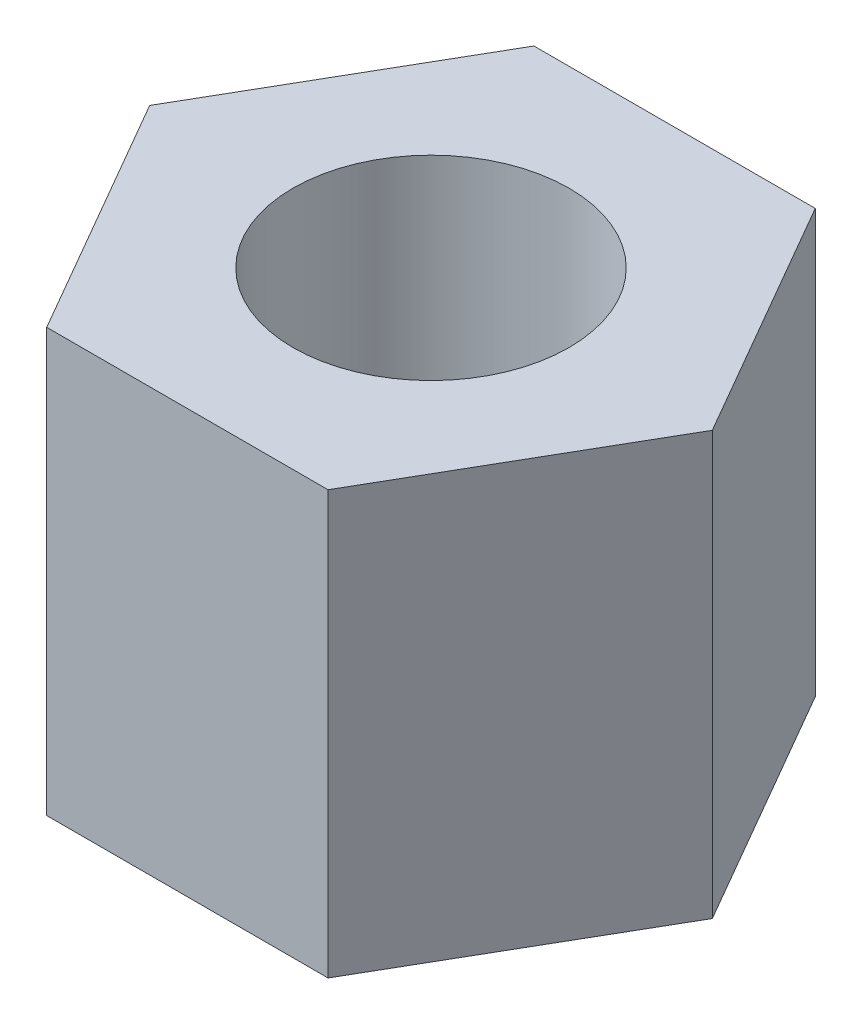
SolidWorks part; units mm, degrees
material "Alloy Steel"
ref_plane "Front" through (0, 0, 0) normal (0, 0, 1) x (1, 0, 0)
ref_plane "Top" through (0, 0, 0) normal (0, 1, 0) x (1, 0, 0)
ref_plane "Right" through (0, 0, 0) normal (1, 0, 0) x (0, 0, -1)
sketch "Sketch1" plane through (0, 0, 0) normal (0, 1, 0) x (1, 0, 0)
  line L1 (3.4641, 6) -> (-3.4641, 6)
  line L2 (-3.4641, 6) -> (-6.9282, 0)
  line L3 (-6.9282, 0) -> (-3.4641, -6)
  line L4 (-3.4641, -6) -> (3.4641, -6)
  line L5 (3.4641, -6) -> (6.9282, 0)
  line L6 (6.9282, 0) -> (3.4641, 6)
  circle A0 centre (0, 0) radius 6 construction
  dimension "D1" = 12
extrude "Extrude1" add sketch "Sketch1" along normal blind 10.414
hole_wizard "M8x1.25 Tapped Hole1" positions "Sketch3" profile "Sketch2" tap size "M8x1.25" standard "Ansi Metric" end condition through all
sketch "Sketch3" plane through (0, 10.414, 0) normal (0, 1, 0) x (-1, 0, 0)
  point P0 (0, 0)
sketch "Sketch2" plane through (0, 10.414, 0) normal (1, 0, 0) x (0, 0, 1)
  line L0 (0, 0) -> (0, 10.414)
  line L1 (0, 10.414) -> (3.4, 10.414)
  line L2 (3.4, 10.414) -> (3.4, 0)
  line L5 (3.4, 0) -> (0, 0)
  line L11 (0, -6.35) -> (0, 107.95) construction
  dimension "Thru Tap Drill Dia." = 6.8
  dimension "Thru Tap Drill Depth" = 10.414
cosmetic thread "Cosmetic Thread1" parameters "D2"=8
